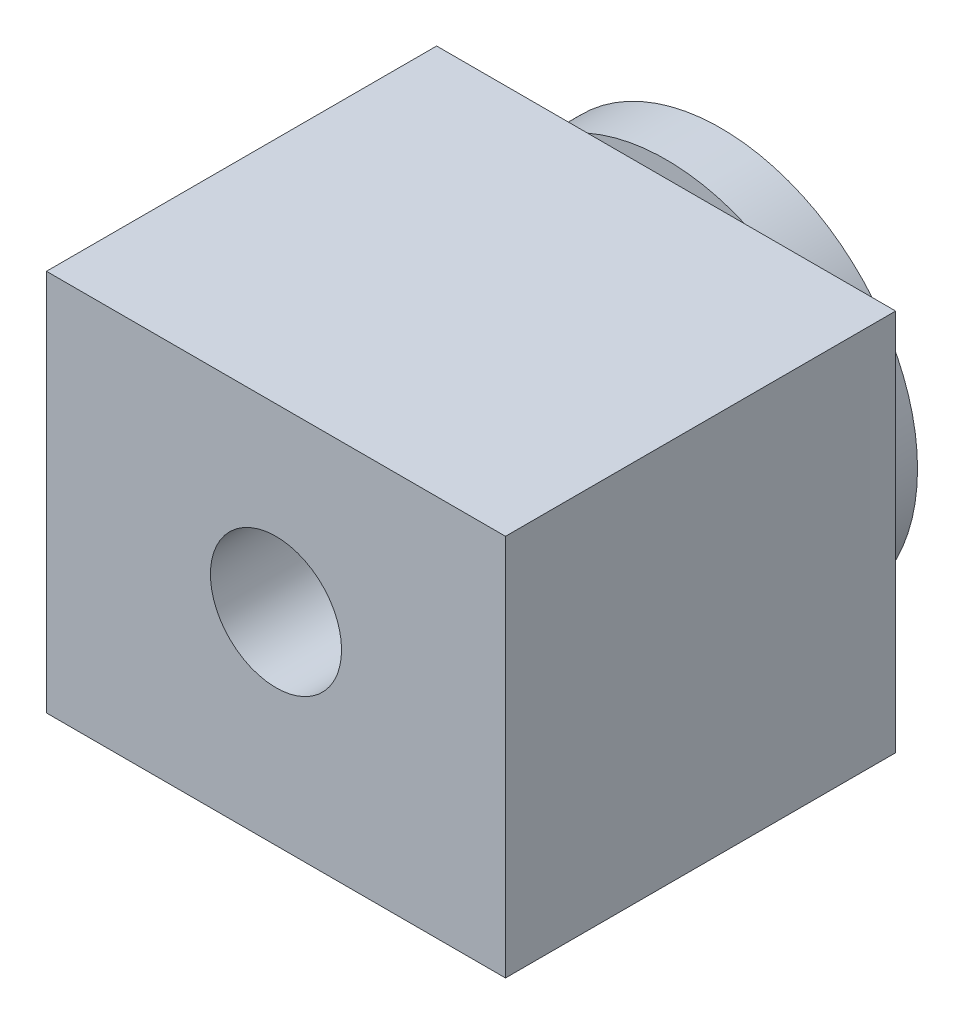
SolidWorks part; units mm, degrees
ref_plane "前视基准面" through (0, 0, 0) normal (0, 0, 1) x (1, 0, 0)
ref_plane "上视基准面" through (0, 0, 0) normal (0, 1, 0) x (1, 0, 0)
ref_plane "右视基准面" through (0, 0, 0) normal (1, 0, 0) x (0, 0, -1)
sketch "草图1" plane through (0, 0, 0) normal (0, 0, 1) x (1, 0, 0)
  circle A0 centre (0, 0) radius 6
  circle A1 centre (0, 0) radius 18
  dimension "D1" = 12
  dimension "D2" = 36
extrude "凸台-拉伸1" add sketch "草图1" along normal blind 5
sketch "草图2" plane through (0, 0, 5) normal (0, 0, 1) x (1, 0, 0)
  line L0 (0, 0) -> (0, -22.9425) construction
  line L1 (0, 27.7861) -> (0, 0) construction
  line L2 (21, -18.5) -> (-21, -18.5)
  line L3 (21, -18.5) -> (21, 16.5)
  line L4 (21, 16.5) -> (-21, 16.5)
  line L5 (-21, -18.5) -> (-21, 16.5)
  line L6 (21, -18.5) -> (-21, 16.5) construction
  line L7 (21, 16.5) -> (-21, -18.5) construction
  circle A0 centre (0, 0) radius 18 construction
  circle A1 centre (0, 0) radius 6 construction
  circle A2 centre (0, 0) radius 6
  point P3 (0, -1)
  point P8 (0, 18)
  point P12 (0, 0)
  dimension "D1" = 42
  dimension "D2" = 35
  dimension "D3" = 1.5
extrude "凸台-拉伸2" add sketch "草图2" along normal blind 35.7
